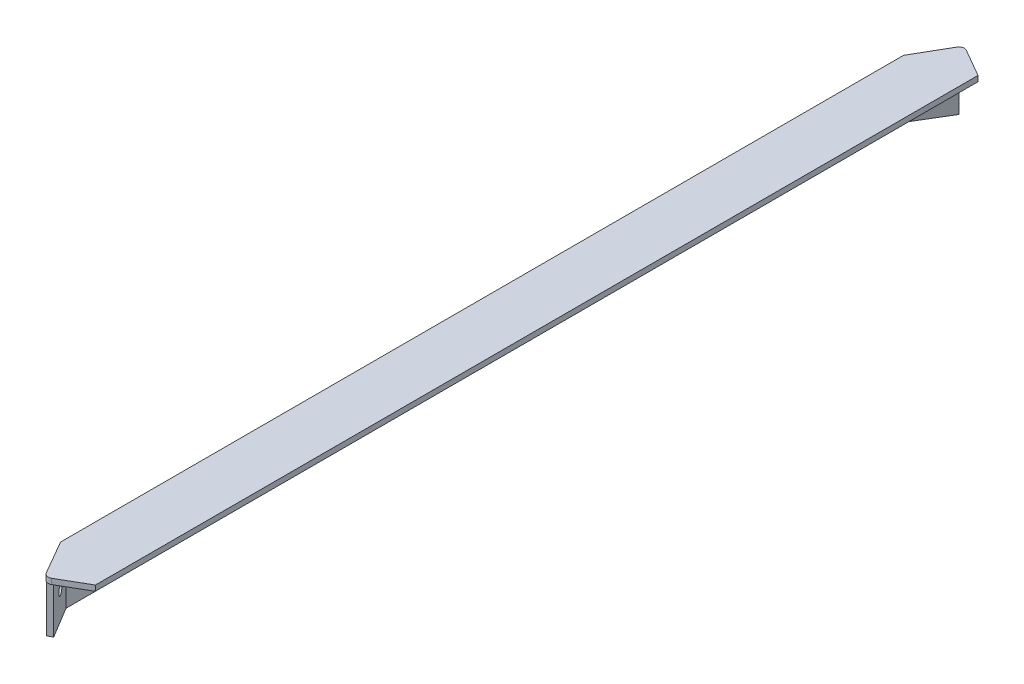
SolidWorks part; units mm, degrees
material "1.0116 (S235J2G3)"
ref_plane "Front Plane" through (0, 0, 0) normal (0, 0, 1) x (1, 0, 0)
ref_plane "Top Plane" through (0, 0, 0) normal (0, 1, 0) x (1, 0, 0)
ref_plane "Right Plane" through (0, 0, 0) normal (1, 0, 0) x (0, 0, -1)
sketch "Sketch1" plane through (0, 0, 0) normal (0, 0, 1) x (1, 0, 0)
  line L6 (0, 0) -> (0, 70)
  line L7 (0, 70) -> (70, 70)
  line L8 (70, 70) -> (70, 63)
  line L9 (70, 63) -> (7, 63)
  line L10 (7, 63) -> (7, 0)
  line L11 (7, 0) -> (0, 0)
  dimension "D1" = 70
  dimension "D2" = 70
  dimension "D3" = 7
  dimension "D4" = 7
extrude "Boss-Extrude1" add sketch "Sketch1" along normal blind 540
sketch "Sketch2" plane through (0, 0, 0) normal (0, 1, 0) x (1, 0, 0)
  line L0 (0, -540) -> (25, -583.3013)
  line L1 (25, -583.3013) -> (31.0622, -579.8013)
  line L2 (31.0622, -579.8013) -> (7, -540)
  line L3 (0, -540) -> (7, -540) construction
  line L4 (7, -540) -> (0, -540)
  line L5 (0, -540) -> (0, 0) construction
  dimension "D1" = 46.5095
  dimension "D2" = 50
  dimension "D3" = 210
  dimension "D4" = 7
extrude "Boss-Extrude2" add sketch "Sketch2" along normal blind 63
sketch "Sketch9" plane through (0, 63, 0) normal (0, 1, 0) x (1, 0, 0)
  line L0 (0, -540) -> (25, -583.3013)
  line L1 (34.5622, -585.8634) -> (70, -565.4034)
  line L2 (70, -565.4034) -> (70, -540)
  line L3 (70, -540) -> (0, -540)
  arc A0 (25, -583.3013) -> (34.5622, -585.8634) centre (31.0622, -579.8013) ccw
  dimension "D5" = 14
  dimension "D2" = 40.9201
  dimension "D1" = 90
  dimension "D3" = 90
  dimension "D4" = 60
  dimension "D6" = 7
  dimension "D7" = 7
extrude "Boss-Extrude4" add sketch "Sketch9" along normal blind 7
sketch "Sketch10" plane through (-233.9536, 0, 141.4385) normal (0.8558, 0, -0.5174) x (-0.5174, 0, -0.8558)
  line L0 (-512.2453, 63) -> (-512.2453, 0) construction
  line L1 (-512.2453, 0) -> (-465.7359, 0) construction
  circle A0 centre (-487.2453, 35) radius 6
  dimension "D1" = 12
  dimension "D2" = 25
  dimension "D3" = 35
extrude "Cut-Extrude3" cut sketch "Sketch10" against normal blind 7
sketch "Sketch21" plane through (0, 0, 0) normal (0, 0, -1) x (-1, 0, 0)
  line L0 (0, 70) -> (-70, 70) construction
  line L1 (-70, 70) -> (-70, 0) construction
  line L2 (-70, 0) -> (0, 0) construction
  line L3 (0, 0) -> (0, 69.2595) construction
fillet "Fillet5" radius 5 2 edges at (19.0311, 63, 559.9006) (7, 63, 270)
mirror "Mirror6" about plane through (0, 0, 0) normal (0, 0, 1) of bodies 107 108
